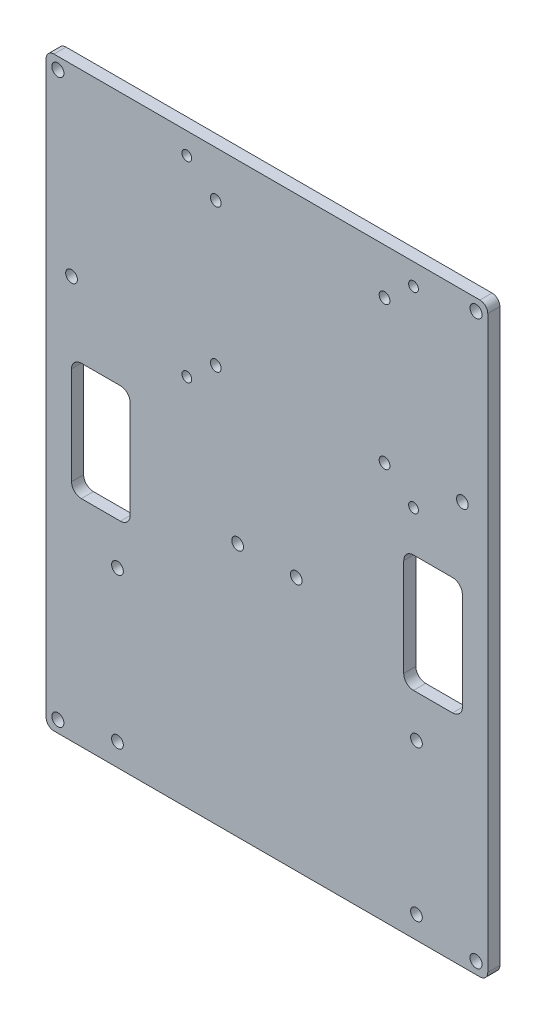
SolidWorks part; units mm, degrees
material "1023 Carbon Steel Sheet (SS)"
ref_plane "Front Plane" through (0, 0, 0) normal (0, 0, 1) x (1, 0, 0)
ref_plane "Top Plane" through (0, 0, 0) normal (0, 1, 0) x (1, 0, 0)
ref_plane "Right Plane" through (0, 0, 0) normal (1, 0, 0) x (0, 0, -1)
sketch "Sketch1" plane through (0, 0, 0) normal (0, 0, 1) x (1, 0, 0)
  line L1 (-56.5, 75) -> (56.5, 75)
  line L2 (-56.5, 75) -> (-56.5, -75)
  line L3 (-56.5, -75) -> (56.5, -75)
  line L4 (56.5, 75) -> (56.5, -75)
  line L5 (-56.5, 75) -> (56.5, -75) construction
  line L6 (-56.5, -75) -> (56.5, 75) construction
  point P0 (0, 0)
  dimension "D1" = 113
  dimension "D2" = 150
extrude "Boss-Extrude1" add sketch "Sketch1" along normal blind 3.1 contours L3 L4 L1 L2
sketch "Sketch3" plane through (0, 0, 3.1) normal (0, 0, 1) x (1, 0, 0)
  line L0 (-56.5, -75) -> (-25.5, -75)
  line L1 (-56.5, 75) -> (-56.5, -75) construction
  line L2 (-56.5, -75) -> (56.5, -75) construction
  line L3 (-25.5, -75) -> (-25.5, -10)
  line L4 (-42.5, -10) -> (-8.5, -10)
  line L5 (-37.5, -36.5) -> (-52.5, -36.5)
  line L6 (-25.5, -10) -> (-37.5, -10)
  line L7 (-25.5, -10) -> (-25.5, -36.5)
  line L8 (-25.5, -36.5) -> (-37.5, -36.5)
  line L9 (-37.5, -10) -> (-37.5, -36.5)
  line L10 (-52.5, -25.5) -> (-52.5, -47.5)
  circle A0 centre (-42.5, -10) radius 1.5
  circle A1 centre (-8.5, -10) radius 1.5
  circle A2 centre (-52.5, -25.5) radius 1.5
  circle A3 centre (-52.5, -47.5) radius 1.5
  point P10 (-25.5, -10)
  point P19 (-52.5, -36.5)
  dimension "D1" = 3
  dimension "D2" = 3
  dimension "D8" = 3
  dimension "D9" = 3
  dimension "D3" = 34
  dimension "D4" = 26.5
  dimension "D5" = 12
  dimension "D6" = 15
  dimension "D7" = 22
  dimension "D10" = 65
  dimension "D11" = 31
extrude "Cut-Extrude1" [suppressed] cut sketch "Sketch3" against normal blind 2.5 contours A1 | A0 | A2 | A3
mirror "Mirror1" [suppressed] about plane through (0, 0, 0) normal (1, 0, 0)
sketch "Sketch6" plane through (0, 0, 3.1) normal (0, 0, 1) x (1, 0, 0)
  line L0 (56.5, -75) -> (36.5, -75)
  line L1 (-56.5, -75) -> (56.5, -75) construction
  line L2 (36.5, -75) -> (36.5, -67)
  line L3 (36.5, -67) -> (-38.64, -67)
  line L4 (36.5, -67) -> (36.5, -18.74)
  line L5 (36.5, -18.74) -> (-14.3, -18.74)
  line L6 (-14.3, -18.74) -> (-14.3, -23.84)
  line L7 (-14.3, -18.74) -> (-44.78, -18.74)
  line L8 (36.5, -18.74) -> (37.77, -18.74)
  line L9 (-14.3, -23.84) -> (-14.3, -51.74)
  circle A0 centre (36.5, -67) radius 1.6
  circle A1 centre (-38.64, -67) radius 1.6
  circle A3 centre (-14.3, -23.84) radius 1.6
  circle A4 centre (-44.78, -18.74) radius 1.6
  circle A5 centre (37.77, -18.74) radius 1.6
  circle A6 centre (-14.3, -51.74) radius 1.6
  dimension "D3" = 3.2
  dimension "D5" = 3.2
  dimension "D7" = 1.27
  dimension "D10" = 3.2
  dimension "D12" = 3.2
  dimension "D13" = 3.2
  dimension "D15" = 3.2
  dimension "D1" = 20
  dimension "D2" = 8
  dimension "D4" = 75.14
  dimension "D6" = 48.26
  dimension "D8" = 50.8
  dimension "D9" = 5.1
  dimension "D11" = 30.48
  dimension "D14" = 27.9
extrude "Cut-Extrude4" [suppressed] cut sketch "Sketch6" against normal through all
sketch "Sketch7" plane through (0, 0, 3.1) normal (0, 0, 1) x (1, 0, 0)
  line L0 (-56.5, 75) -> (-18.5, 75)
  line L1 (-56.5, 75) -> (56.5, 75) construction
  line L2 (-18.5, 75) -> (-18.5, 35)
  line L3 (-18.5, 35) -> (-52.5, 35)
  line L4 (-52.5, 57.5) -> (-52.5, 12.5)
  line L5 (-54, 65) -> (-51, 65)
  line L6 (-54, 20) -> (-51, 20)
  line L7 (-54, 20) -> (-54, 5)
  line L8 (-54, 5) -> (-51, 5)
  line L9 (-51, 20) -> (-51, 5)
  line L10 (-54, 20) -> (-51, 5) construction
  line L11 (-54, 5) -> (-51, 20) construction
  line L12 (-51, 50) -> (-51, 65)
  line L13 (-54, 50) -> (-51, 50)
  line L14 (-54, 50) -> (-54, 65)
  line L15 (17, 5) -> (14, 5)
  line L16 (14, 20) -> (14, 5)
  line L17 (17, 20) -> (14, 20)
  line L18 (17, 20) -> (17, 5)
  line L19 (17, 50) -> (17, 65)
  line L20 (17, 50) -> (14, 50)
  line L21 (14, 50) -> (14, 65)
  line L22 (17, 65) -> (14, 65)
  point P10 (-52.5, 35)
  dimension "D1" = 38
  dimension "D2" = 40
  dimension "D3" = 45
  dimension "D4" = 15
  dimension "D5" = 3
  dimension "D6" = 34
extrude "Cut-Extrude5" [suppressed] cut sketch "Sketch7" against normal through all contours L12 L5 L14 L13 | L19 L22 L21 L20 | L18 L15 L16 L17 | L9 L8 L7 L6
sketch "Sketch8" plane through (0, 0, 3.1) normal (0, 0, 1) x (1, 0, 0)
  line L0 (-56.5, 75) -> (56.5, 75) construction
  line L1 (0, 75) -> (0, 49)
  circle A0 centre (0, 49) radius 1.55
  dimension "D2" = 3.1
  dimension "D1" = 26
extrude "Cut-Extrude6" [suppressed] cut sketch "Sketch8" against normal through all contours A0
chamfer "Chamfer1" [suppressed] distance 1.5 angle 45
sketch "Sketch9" plane through (0, 0, 3.1) normal (0, 0, 1) x (1, 0, 0)
  line L1 (-53.5, 72) -> (53.5, 72)
  line L2 (-53.5, 72) -> (-53.5, -72)
  line L3 (-53.5, -72) -> (53.5, -72)
  line L4 (53.5, 72) -> (53.5, -72)
  line L5 (-53.5, 72) -> (53.5, -72) construction
  line L6 (-53.5, -72) -> (53.5, 72) construction
  circle A0 centre (-53.5, 72) radius 1.55
  circle A1 centre (53.5, 72) radius 1.55
  circle A2 centre (53.5, -72) radius 1.55
  circle A3 centre (-53.5, -72) radius 1.55
  point P0 (0, 0)
  dimension "D3" = 3.1
  dimension "D1" = 107
  dimension "D2" = 144
extrude "Cut-Extrude7" cut sketch "Sketch9" against normal through all contours A0 | A1 | A2 | A3
sketch "Sketch10" plane through (0, 0, 3.1) normal (0, 0, 1) x (1, 0, 0)
  line L0 (-56.5, 75) -> (8.5, 75)
  line L1 (-56.5, 75) -> (56.5, 75) construction
  line L2 (8.5, 75) -> (8.5, 45)
  line L4 (-20.5, 69.5) -> (37.5, 69.5)
  line L5 (-20.5, 69.5) -> (-20.5, 20.5)
  line L6 (-20.5, 20.5) -> (37.5, 20.5)
  line L7 (37.5, 69.5) -> (37.5, 20.5)
  line L8 (-20.5, 69.5) -> (37.5, 20.5) construction
  line L9 (-20.5, 20.5) -> (37.5, 69.5) construction
  circle A0 centre (-20.5, 69.5) radius 1.25
  circle A1 centre (37.5, 69.5) radius 1.25
  circle A2 centre (37.5, 20.5) radius 1.25
  circle A3 centre (-20.5, 20.5) radius 1.25
  point P5 (8.5, 45)
  dimension "D4" = 2.5
  dimension "D1" = 65
  dimension "D2" = 49
  dimension "D3" = 58
  dimension "D5" = 30
extrude "Cut-Extrude8" cut sketch "Sketch10" against normal through all contours L6 A2 L7 | A0 | A1 | A3
sketch "Sketch12" plane through (0, 0, 3.1) normal (0, 0, 1) x (1, 0, 0)
  line L0 (-56.5, -75) -> (0, -75) construction
  line L1 (-56.5, -75) -> (56.5, -75) construction
  line L2 (0, -75) -> (0, -50) construction
  line L4 (-38.25, -30.75) -> (38.25, -30.75) construction
  line L5 (-38.25, -30.75) -> (-38.25, -69.25) construction
  line L6 (-38.25, -69.25) -> (38.25, -69.25) construction
  line L7 (38.25, -30.75) -> (38.25, -69.25) construction
  line L8 (-38.25, -30.75) -> (38.25, -69.25) construction
  line L9 (-38.25, -69.25) -> (38.25, -30.75) construction
  circle A0 centre (-38.25, -30.75) radius 1.5
  circle A1 centre (-38.25, -69.25) radius 1.5
  circle A2 centre (38.25, -69.25) radius 1.5
  circle A3 centre (38.25, -30.75) radius 1.5
  dimension "D5" = 3
  dimension "D1" = 56.5
  dimension "D2" = 25
  dimension "D3" = 38.5
  dimension "D4" = 76.5
extrude "Cut-Extrude9" cut sketch "Sketch12" against normal through all
sketch "Sketch13" plane through (0, 0, 3.1) normal (0, 0, 1) x (1, 0, 0)
  line L0 (-56.5, -75) -> (0, -75) construction
  line L1 (-56.5, -75) -> (56.5, -75) construction
  line L2 (0, -75) -> (0, -10) construction
  line L3 (-7.5, -10) -> (7.5, -10) construction
  circle A0 centre (-7.5, -10) radius 1.5
  circle A1 centre (7.5, -10) radius 1.5
  point P9 (0, -10)
  dimension "D4" = 3
  dimension "D1" = 56.5
  dimension "D2" = 65
  dimension "D3" = 15
extrude "Cut-Extrude10" cut sketch "Sketch13" against normal through all
sketch "Sketch14" plane through (0, 0, 3.1) normal (0, 0, 1) x (1, 0, 0)
  line L0 (-56.5, -75) -> (0, -75) construction
  line L1 (-56.5, -75) -> (56.5, -75) construction
  line L2 (0, -75) -> (0, -5) construction
  line L3 (-42.5, -5) -> (42.5, -5) construction
  line L5 (-50, 10) -> (-35, 10)
  line L6 (-50, 10) -> (-50, -20)
  line L7 (-50, -20) -> (-35, -20)
  line L8 (-35, 10) -> (-35, -20)
  line L9 (-50, 10) -> (-35, -20) construction
  line L10 (-50, -20) -> (-35, 10) construction
  line L11 (35, 10) -> (50, 10)
  line L12 (35, 10) -> (35, -20)
  line L13 (35, -20) -> (50, -20)
  line L14 (50, 10) -> (50, -20)
  line L15 (35, 10) -> (50, -20) construction
  line L16 (35, -20) -> (50, 10) construction
  point P10 (0, -5)
  dimension "D1" = 56.5
  dimension "D2" = 85
  dimension "D3" = 70
  dimension "D4" = 30
  dimension "D5" = 15
extrude "Cut-Extrude11" cut sketch "Sketch14" against normal through all contours L14 L11 L12 L13 | L8 L7 L6 L5
sketch "Sketch16" plane through (0, 0, 0) normal (0, 0, -1) x (-1, 0, 0)
  line L0 (56.5, 75) -> (-8.5, 75) construction
  line L1 (56.5, 75) -> (-56.5, 75) construction
  line L2 (-8.5, 75) -> (-8.5, 45) construction
  line L4 (-30.09, 63.29) -> (13.09, 63.29) construction
  line L5 (-30.09, 63.29) -> (-30.09, 26.71) construction
  line L6 (-30.09, 26.71) -> (13.09, 26.71) construction
  line L7 (13.09, 63.29) -> (13.09, 26.71) construction
  line L8 (-30.09, 63.29) -> (13.09, 26.71) construction
  line L9 (-30.09, 26.71) -> (13.09, 63.29) construction
  circle A0 centre (-30.09, 63.29) radius 1.375
  circle A1 centre (-30.09, 26.71) radius 1.375
  circle A2 centre (13.09, 63.29) radius 1.375
  circle A3 centre (13.09, 26.71) radius 1.375
  dimension "D5" = 2.75
  dimension "D1" = 65
  dimension "D2" = 30
  dimension "D3" = 43.18
  dimension "D4" = 36.58
extrude "Cut-Extrude12" cut sketch "Sketch16" against normal through all contours A1 | A3 | A2 | A0
sketch "Sketch18" plane through (0, 0, 3.1) normal (0, 0, 1) x (1, 0, 0)
  line L0 (-56.5, 75) -> (0, 75) construction
  line L1 (-56.5, 75) -> (56.5, 75) construction
  line L2 (0, 75) -> (0, 28) construction
  line L3 (-50, 28) -> (50, 28) construction
  circle A0 centre (-50, 28) radius 1.5
  circle A1 centre (50, 28) radius 1.5
  point P9 (0, 28)
  dimension "D4" = 3
  dimension "D1" = 56.5
  dimension "D2" = 47
  dimension "D3" = 100
extrude "Cut-Extrude13" cut sketch "Sketch18" against normal through all
fillet "Fillet1" radius 2 4 edges at (56.5, -75, 1.55) (-56.5, -75, 1.55) (56.5, 75, 1.55) (-56.5, 75, 1.55)
fillet "Fillet2" radius 2.5 8 edges at (50, -20, 1.55) (50, 10, 1.55) (35, 10, 1.55) (35, -20, 1.55) (-50, -20, 1.55) (-35, -20, 1.55) (-35, 10, 1.55) (-50, 10, 1.55)
